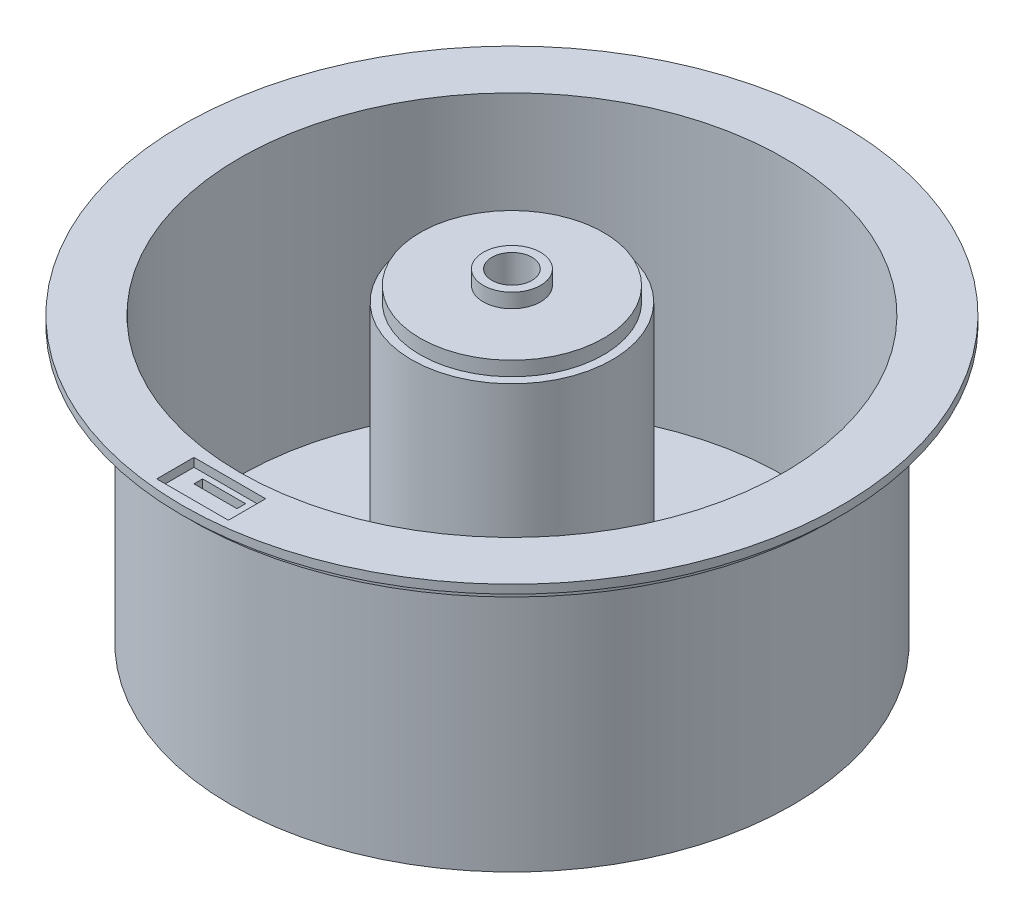
SolidWorks part; units mm, degrees
ref_plane "Front Plane" through (0, 0, 0) normal (0, 0, 1) x (1, 0, 0)
ref_plane "Top Plane" through (0, 0, 0) normal (0, 1, 0) x (1, 0, 0)
ref_plane "Right Plane" through (0, 0, 0) normal (1, 0, 0) x (0, 0, -1)
sketch "Sketch2" plane through (0, 0, 0) normal (0, 1, 0) x (1, 0, 0)
  circle A0 centre (0, 0) radius 115
  dimension "D1" = 230
extrude "Boss-Extrude1" add sketch "Sketch2" along normal blind 3
sketch "Sketch3" plane through (0, 0, 0) normal (0, -1, 0) x (-1, 0, 0)
  circle A0 centre (0, 0) radius 112
  circle A1 centre (0, 0) radius 115 construction
  dimension "D1" = 3
extrude "Boss-Extrude2" add sketch "Sketch3" along normal blind 3
sketch "Sketch4" plane through (0, -3, 0) normal (0, -1, 0) x (1, 0, 0)
  circle A0 centre (0, 0) radius 98
  circle A1 centre (0, 0) radius 115 construction
  dimension "D1" = 17
extrude "Boss-Extrude3" add sketch "Sketch4" along normal blind 93 contours A0
sketch "Sketch5" plane through (0, 3, 0) normal (0, 1, 0) x (1, 0, 0)
  circle A0 centre (0, 0) radius 95
  circle A1 centre (0, 0) radius 115 construction
  dimension "D1" = 20
extrude "Cut-Extrude1" cut sketch "Sketch5" against normal blind 96
sketch "Sketch6" plane through (0, -93, 0) normal (0, 1, 0) x (1, 0, 0)
  circle A0 centre (0, 0) radius 35
  dimension "D1" = 70
extrude "Boss-Extrude4" add sketch "Sketch6" along normal blind 100
sketch "Sketch7" plane through (0, 7, 0) normal (0, 1, 0) x (1, 0, 0)
  circle A0 centre (0, 0) radius 32
  circle A1 centre (0, 0) radius 35 construction
  dimension "D1" = 3
extrude "Boss-Extrude5" add sketch "Sketch7" along normal blind 5
sketch "Sketch8" plane through (0, -96, 0) normal (0, -1, 0) x (1, 0, 0)
  circle A0 centre (0, 0) radius 32
  dimension "D1" = 64
extrude "Cut-Extrude2" cut sketch "Sketch8" against normal blind 99
sketch "Sketch9" plane through (0, 3, 0) normal (0, -1, 0) x (1, 0, 0)
  circle A0 centre (0, 0) radius 28
  dimension "D1" = 56
extrude "Cut-Extrude3" cut sketch "Sketch9" against normal blind 4
sketch "Sketch10" plane through (0, 12, 0) normal (0, 1, 0) x (1, 0, 0)
  circle A0 centre (0, 0) radius 10
  dimension "D1" = 20
extrude "Boss-Extrude8" add sketch "Sketch10" along normal blind 5 contours A0
sketch "Sketch11" plane through (0, 17, 0) normal (0, 1, 0) x (1, 0, 0)
  circle A0 centre (0, 0) radius 7
  circle A1 centre (0, 0) radius 10 construction
  dimension "D1" = 3
extrude "Cut-Extrude4" cut sketch "Sketch11" against normal blind 35
sketch "Sketch12" plane through (0, 0, 0) normal (0, 1, 0) x (1, 0, 0)
  line L0 (0, 0) -> (0, -126.3103) construction
ref_plane "Plane3" through (0, 10, 0) normal (0, 1, 0) x (1, 0, 0)
sketch "Sketch13" plane through (0, 10, 0) normal (0, 1, 0) x (1, 0, 0)
  line L0 (0, 0) -> (0, -126.3103) construction
  line L1 (-12.5, -98.4503) -> (12.5, -98.4503)
  line L2 (-12.5, -98.4503) -> (-12.5, -111.4503)
  line L3 (-12.5, -111.4503) -> (12.5, -111.4503)
  line L4 (12.5, -98.4503) -> (12.5, -111.4503)
  line L5 (-12.5, -98.4503) -> (12.5, -111.4503) construction
  line L6 (-12.5, -111.4503) -> (12.5, -98.4503) construction
  point P0 (0, -104.9503)
  dimension "D1" = 25
  dimension "D2" = 13
extrude "Cut-Extrude5" cut sketch "Sketch13" against normal blind 10
sketch "Sketch14" plane through (0, 0, 0) normal (0, 1, 0) x (1, 0, 0)
  line L0 (0, 0) -> (0, -126.3103) construction
  line L1 (-7.5, -100.4503) -> (7.5, -100.4503)
  line L2 (-7.5, -100.4503) -> (-7.5, -103.4503)
  line L3 (-7.5, -103.4503) -> (7.5, -103.4503)
  line L4 (7.5, -100.4503) -> (7.5, -103.4503)
  line L5 (-7.5, -100.4503) -> (7.5, -103.4503) construction
  line L6 (-7.5, -103.4503) -> (7.5, -100.4503) construction
  line L7 (12.5, -98.4503) -> (-12.5, -98.4503) construction
  point P0 (0, -101.9503)
  dimension "D1" = 15
  dimension "D2" = 3
  dimension "D3" = 2
extrude "Cut-Extrude7" cut sketch "Sketch14" against normal blind 10
